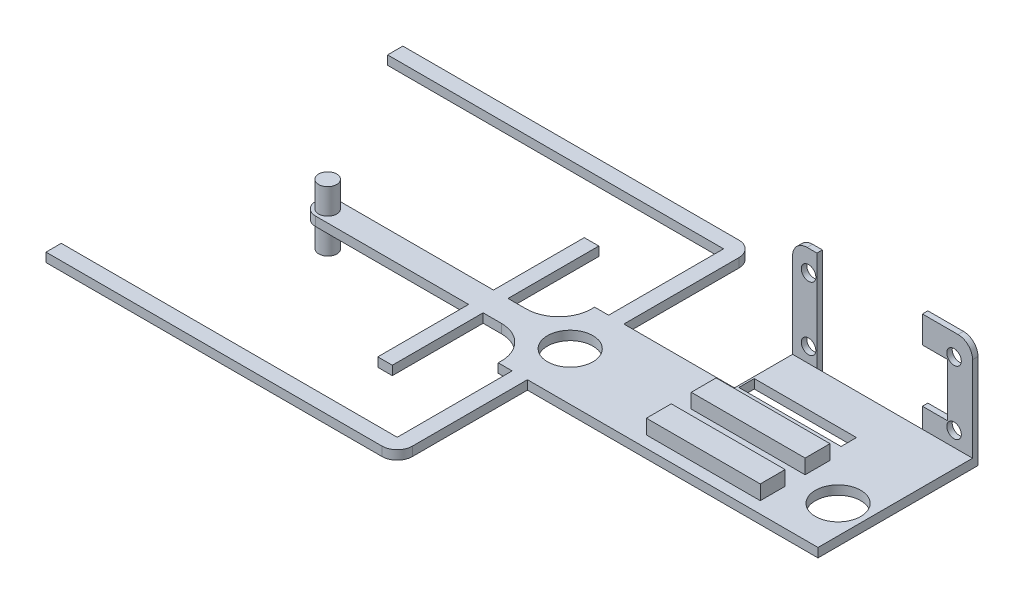
SolidWorks part; units mm, degrees
ref_plane "Front Plane" through (0, 0, 0) normal (0, 0, 1) x (1, 0, 0)
ref_plane "Top Plane" through (0, 0, 0) normal (0, 1, 0) x (1, 0, 0)
ref_plane "Right Plane" through (0, 0, 0) normal (1, 0, 0) x (0, 0, -1)
sketch "Sketch1" plane through (0, 0, 0) normal (0, 1, 0) x (1, 0, 0)
  line L0 (0, 5.14) -> (0, 5.31)
  line L1 (0, 0) -> (17.61, 0)
  line L2 (0, 0) -> (0, 0.17)
  line L3 (7.7, 8.51) -> (17.61, 8.51)
  line L4 (17.61, 0) -> (17.61, 8.51)
  line L6 (0.77, 11.64) -> (0.77, 5.31)
  line L7 (0, 5.31) -> (7.7, 5.31)
  line L8 (7.7, 8.51) -> (7.7, 5.31)
  line L9 (7.7, 8.51) -> (9.04, 8.51)
  line L10 (7.7, 8.51) -> (7.7, 8.81)
  line L11 (7.7, 8.81) -> (9.04, 8.81)
  line L12 (9.04, 8.51) -> (9.04, 8.81)
  line L13 (17.61, 8.51) -> (14.85, 8.51)
  line L14 (17.61, 8.51) -> (17.61, 8.81)
  line L15 (17.61, 8.81) -> (14.85, 8.81)
  line L16 (14.85, 8.51) -> (14.85, 8.81)
  line L17 (7.8, 6.3) -> (13.43, 6.3)
  line L18 (7.8, 6.3) -> (7.8, 5.45)
  line L19 (7.8, 5.45) -> (13.43, 5.45)
  line L20 (13.43, 6.3) -> (13.43, 5.45)
  line L21 (7.52, 4.48) -> (13.79, 4.48)
  line L22 (7.52, 4.48) -> (7.52, 3.11)
  line L23 (7.52, 3.11) -> (13.79, 3.11)
  line L24 (13.79, 4.48) -> (13.79, 3.11)
  line L25 (7.52, 2.01) -> (13.79, 2.01)
  line L26 (7.52, 2.01) -> (7.52, 0.64)
  line L27 (7.52, 0.64) -> (13.79, 0.64)
  line L28 (13.79, 2.01) -> (13.79, 0.64)
  line L29 (0.77, 5.31) -> (1.61, 5.31)
  line L30 (1.61, 11.64) -> (1.61, 5.31)
  line L31 (0.77, 0) -> (1.61, 0)
  line L32 (0.77, 0) -> (0.77, -6.33)
  line L34 (1.61, 0) -> (1.61, -6.33)
  line L35 (-12.035, 3.34) -> (-1.8, 3.34)
  line L37 (-12.035, 1.97) -> (-1.8, 1.97)
  line L38 (0.77, 12.48) -> (-17.73, 12.48)
  line L40 (0.77, 11.64) -> (-17.73, 11.64)
  line L41 (-17.73, 12.48) -> (-17.73, 11.64)
  line L42 (0.77, -7.17) -> (-17.73, -7.17)
  line L44 (0.77, -6.33) -> (-17.73, -6.33)
  line L45 (-17.73, -7.17) -> (-17.73, -6.33)
  circle A0 centre (1.31, 2.655) radius 1.25
  circle A1 centre (16.06, 2.655) radius 1.25
  arc A2 (-1.8, 3.34) -> (0, 5.14) centre (-1.8, 5.14) ccw
  arc A3 (0, 0.17) -> (-1.8, 1.97) centre (-1.8, 0.17) ccw
  circle A4 centre (-12.035, 2.655) radius 0.5
  circle A5 centre (-12.035, 2.655) radius 0.685
  arc A6 (1.61, 11.64) -> (0.77, 12.48) centre (0.77, 11.64) ccw
  arc A7 (0.77, -7.17) -> (1.61, -6.33) centre (0.77, -6.33) ccw
  point P30 (13.79, 1.325)
  dimension "D1" = 8.51
  dimension "D14" = 17.61
  dimension "D15" = 2.655
  dimension "D28" = 16.3
  dimension "D29" = 18.5
  dimension "D2" = 3.82
  dimension "D3" = 3.82
  dimension "D4" = 6.27
  dimension "D5" = 6.27
  dimension "D6" = 1.37
  dimension "D7" = 1.37
  dimension "D8" = 0.64
  dimension "D9" = 1.1
  dimension "D10" = 0.97
  dimension "D11" = 4.18
  dimension "D12" = 5.63
  dimension "D13" = 0.85
  dimension "D16" = 9.91
  dimension "D17" = 5.31
  dimension "D18" = 1.34
  dimension "D19" = 0.3
  dimension "D20" = 2.76
  dimension "D21" = 0.3
  dimension "D22" = 1.55
  dimension "D23" = 0.77
  dimension "D24" = 0.77
  dimension "D27" = 1.97
  dimension "D30" = 18.5
  dimension "D31" = 6.33
  dimension "D33" = 0.84
  dimension "D34" = 6.33
extrude "Boss-Extrude2" add sketch "Sketch1" along normal blind 0.5 contours A5 L37 A3 L2 L1 L4 L3 L8 L7 L0 A2 L35 L25 L28 L27 L26 L21 L24 L23 L22 L17 L20 L19 L18 A0 A1 | L30 A6 L38 L41 L40 L6 L7 | L42 A7 L34 L1 L32 L44 L45 | L28 L25 L26 L27 | L24 L21 L22 L23 | A4 | A5 A4 | L3 L12 L11 L10 | L16 L3 L14 L15
sketch "Sketch4" plane through (0, 0.5, 0) normal (0, 1, 0) x (1, 0, 0)
  line L0 (-12.035, 1.97) -> (-1.8, 1.97) construction
  circle A0 centre (-12.04, 2.65) radius 0.5
  arc A1 (-12.035, 3.34) -> (-12.035, 1.97) centre (-12.035, 2.655) ccw construction
  point P10 (-12.72, 2.655)
  dimension "D1" = 0.68
  dimension "D2" = 0.68
extrude "Boss-Extrude3" add sketch "Sketch4" along normal blind 1.41
sketch "Sketch5" plane through (0, 0, 0) normal (0, -1, 0) x (1, 0, 0)
  line L0 (-12.035, -3.34) -> (-1.8, -3.34) construction
  circle A0 centre (-12.04, -2.66) radius 0.5
  arc A1 (-12.035, -1.97) -> (-12.035, -3.34) centre (-12.035, -2.655) ccw construction
  point P6 (-12.72, -2.655)
  dimension "D1" = 0.68
  dimension "D2" = 0.68
extrude "Boss-Extrude4" add sketch "Sketch5" along normal blind 1.41
sketch "Sketch6" plane through (0, 0.5, 0) normal (0, 1, 0) x (1, 0, 0)
  line L0 (7.8, 5.45) -> (13.43, 5.45) construction
  line L1 (7.52, 4.48) -> (13.79, 4.48)
  line L2 (7.52, 4.48) -> (7.52, 3.11)
  line L3 (7.52, 3.11) -> (13.79, 3.11)
  line L4 (13.79, 4.48) -> (13.79, 3.11)
  line L5 (7.52, 2.01) -> (13.79, 2.01)
  line L6 (7.52, 2.01) -> (7.52, 0.64)
  line L7 (7.52, 0.64) -> (13.79, 0.64)
  line L8 (13.79, 2.01) -> (13.79, 0.64)
  line L9 (17.61, 0) -> (17.61, 8.81) construction
  dimension "D1" = 6.27
  dimension "D2" = 6.27
  dimension "D3" = 1.37
  dimension "D4" = 1.37
  dimension "D5" = 1.1
  dimension "D6" = 0.97
  dimension "D7" = 3.82
extrude "Boss-Extrude5" add sketch "Sketch6" along normal blind 0.8
sketch "Sketch7" plane through (0, 0.5, 0) normal (0, 1, 0) x (1, 0, 0)
  line L0 (17.61, 0) -> (17.61, 8.81) construction
  line L1 (7.7, 8.81) -> (9.04, 8.81)
  line L2 (7.7, 8.81) -> (7.7, 8.51)
  line L3 (7.7, 8.51) -> (9.04, 8.51)
  line L4 (9.04, 8.81) -> (9.04, 8.51)
  line L5 (14.85, 8.81) -> (17.61, 8.81)
  line L6 (14.85, 8.81) -> (14.85, 8.51)
  line L7 (14.85, 8.51) -> (17.61, 8.51)
  line L8 (17.61, 8.81) -> (17.61, 8.51)
extrude "Boss-Extrude6" add sketch "Sketch7" along normal blind 5.5
sketch "Sketch8" plane through (0, 0, -8.51) normal (0, 0, 1) x (1, 0, 0)
  line L0 (14.85, 6) -> (14.85, 0.5) construction
  line L1 (14.85, 4.52) -> (16.23, 4.52)
  line L2 (14.85, 4.52) -> (14.85, 1.6)
  line L3 (14.85, 1.6) -> (16.23, 1.6)
  line L4 (16.23, 4.52) -> (16.23, 1.6)
  line L5 (14.85, 0.5) -> (17.61, 0.5) construction
  dimension "D1" = 1.38
  dimension "D2" = 2.92
  dimension "D3" = 1.1
extrude "Cut-Extrude1" cut sketch "Sketch8" against normal blind 5.5
sketch "Sketch9" plane through (0, 0, -8.51) normal (0, 0, 1) x (1, 0, 0)
  line L0 (9.04, 6) -> (9.04, 0.5) construction
  line L1 (7.7, 0.5) -> (9.04, 0.5) construction
  line L2 (7.7, 6) -> (9.04, 6) construction
  line L3 (7.7, 6) -> (7.7, 0.5) construction
  circle A0 centre (8.58, 4.82) radius 0.4
  circle A1 centre (8.58, 1.32) radius 0.4
  circle A2 centre (8.5, 5.2) radius 0.8
  line M3 (9.04, 6) -> (7.7, 6)
  line M4 (7.7, 6) -> (7.7, 0.5)
  dimension "D1" = 0.46
  dimension "D5" = 1.6
  dimension "D2" = 0.46
  dimension "D3" = 3.5
  dimension "D4" = 0.82
extrude "Cut-Extrude2" cut sketch "Sketch9" against normal blind 5.5 contours A2 M3 M4 | A0 | A1
sketch "Sketch10" plane through (0, 0, -8.51) normal (0, 0, 1) x (1, 0, 0)
  line L0 (14.85, 6) -> (17.61, 6) construction
  line L1 (14.85, 6) -> (14.85, 4.52) construction
  line L2 (17.61, 6) -> (17.61, 0.5) construction
  circle A0 centre (16.59, 4.82) radius 0.4
  circle A1 centre (16.59, 1.32) radius 0.4
  circle A2 centre (16.81, 5.2) radius 0.8
  line M13 (17.61, 0.5) -> (17.61, 6)
  line M14 (17.61, 6) -> (14.85, 6)
  dimension "D2" = 1.18
  dimension "D3" = 1.74
  dimension "D1" = 3.5
extrude "Cut-Extrude4" cut sketch "Sketch10" against normal blind 5.5 contours A2 M13 M14 | A0 A2 | A1
sketch "Sketch11" plane through (0, 0, -1.97) normal (0, 0, 1) x (1, 0, 0)
  line L0 (-12.035, 0.5) -> (-1.8, 0.5) construction
  line L1 (-2.8, 0.5) -> (-3.6, 0.5)
  line L2 (-2.8, 0.5) -> (-2.8, 0)
  line L3 (-2.8, 0) -> (-3.6, 0)
  line L4 (-3.6, 0.5) -> (-3.6, 0)
  line L5 (-12.035, 0) -> (-1.8, 0) construction
  line L6 (-1.8, 0.5) -> (-1.8, 0) construction
  dimension "D1" = 0.8
  dimension "D2" = 1
extrude "Boss-Extrude7" add sketch "Sketch11" along normal blind 5
sketch "Sketch12" plane through (0, 0, -3.34) normal (0, 0, -1) x (-1, 0, 0)
  line L0 (12.035, 0) -> (1.8, 0) construction
  line L1 (3.6, 0) -> (2.8, 0)
  line L2 (3.6, 0) -> (3.6, 0.5)
  line L3 (3.6, 0.5) -> (2.8, 0.5)
  line L4 (2.8, 0) -> (2.8, 0.5)
  line L5 (12.035, 0.5) -> (1.8, 0.5) construction
  line L6 (1.8, 0.5) -> (1.8, 0) construction
  dimension "D1" = 0.8
  dimension "D2" = 1
extrude "Boss-Extrude8" add sketch "Sketch12" along normal blind 5
